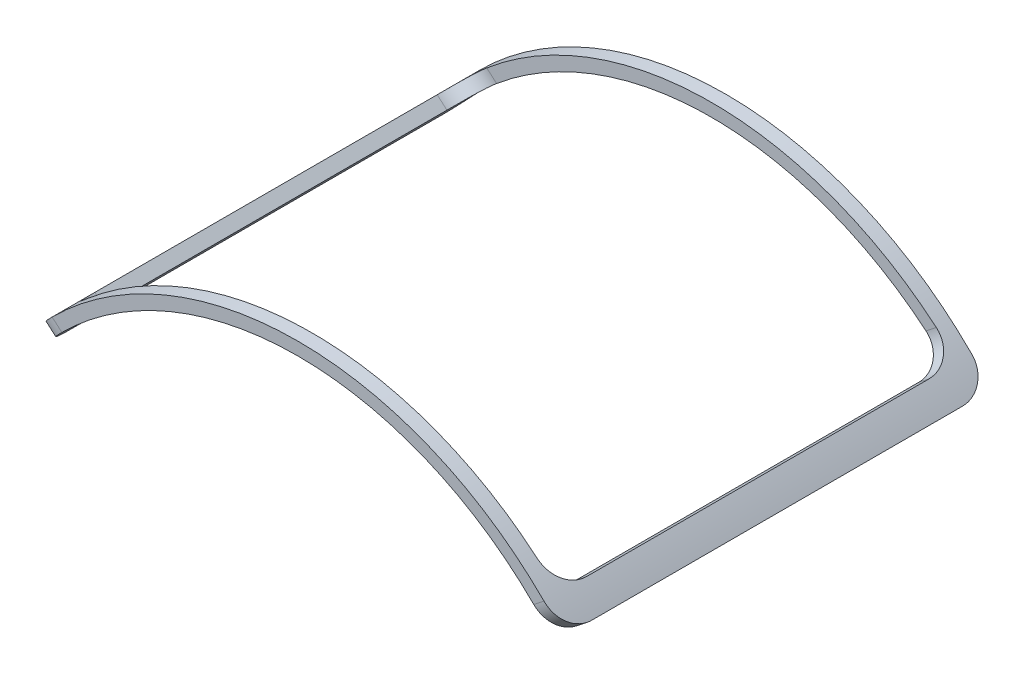
SolidWorks part; units mm, degrees
ref_plane "Front Plane" through (0, 0, 0) normal (0, 0, 1) x (1, 0, 0)
ref_plane "Top Plane" through (0, 0, 0) normal (0, 1, 0) x (1, 0, 0)
ref_plane "Right Plane" through (0, 0, 0) normal (1, 0, 0) x (0, 0, -1)
sketch "Sketch1" plane through (0, 0, 0) normal (0, 0, 1) x (1, 0, 0)
  line L5 (1810, 0) -> (1802.1311, -6.1912)
  line L6 (7.5417, -6.5668) -> (0, 0)
  line L7 (1810, 0) -> (1888.9258, -111.3385) construction
  line L8 (1802.1311, -6.1912) -> (1880.7676, -117.1216) construction
  line L9 (1835.3105, -2.4803) -> (1799.7656, -30.4471)
  line L10 (9.357, -31.4845) -> (-24.735, -1.7992)
  arc A0 (0, 0) -> (1810, 0) centre (905, -788.0197) cw
  arc A1 (7.5417, -6.5668) -> (1802.1311, -6.1912) centre (905, -788.0197) cw
  arc A2 (-24.735, -1.7992) -> (1835.3105, -2.4803) centre (905, -788.0197) cw
  arc A3 (9.357, -31.4845) -> (1799.7656, -30.4471) centre (905, -788.0197) cw
  dimension "D1" = 1200
  dimension "D2" = 1810
  dimension "D3" = 17.6
  dimension "D4" = 10
extrude "Boss-Extrude4" add sketch "Sketch1" along normal blind 1500 contours A2 L9 A3 L10
fillet "Fillet2" radius 100 4 edges at (-7.689, -16.6419, 0) (1817.5381, -16.4637, 0) (1817.5381, -16.4637, 1500) (-7.689, -16.6419, 1500)
ref_plane "Plane1" through (0, 0, 50) normal (0, 0, 1) x (1, 0, 0)
sketch "Sketch2" plane through (0, 0, 50) normal (0, 0, 1) x (1, 0, 0)
  line L0 (1767.5087, 71.4153) -> (1731.732, 43.2661)
  line L1 (42.9425, 71.8679) -> (77.1122, 42.115)
  arc A0 (1767.5087, 71.4153) -> (42.9425, 71.8679) centre (905, -788.0197) ccw construction
  arc A1 (1731.732, 43.2661) -> (77.1122, 42.115) centre (905, -788.0197) ccw construction
  arc A2 (1767.5087, 71.4153) -> (42.9425, 71.8679) centre (905, -788.0197) ccw
  arc A3 (1731.732, 43.2661) -> (77.1122, 42.115) centre (905, -788.0197) ccw
extrude "Cut-Extrude1" cut sketch "Sketch2" along normal blind 1400
fillet "Fillet3" radius 100 4 edges at (1749.6203, 57.3407, 1450) (60.0274, 56.9914, 1450) (60.0274, 56.9914, 50) (1749.6203, 57.3407, 50)
